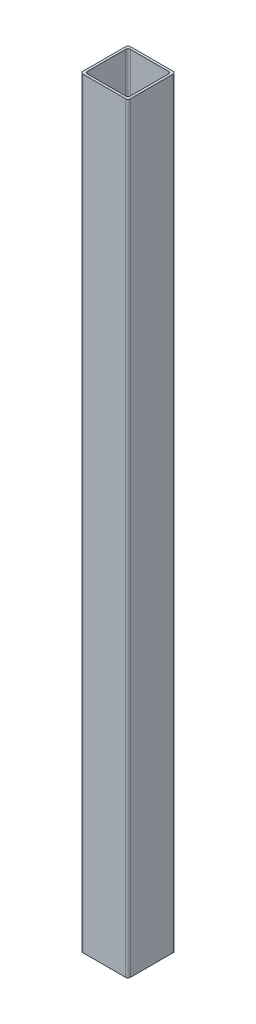
SolidWorks part; units mm, degrees
ref_plane "Спереди" through (0, 0, 0) normal (0, 0, 1) x (1, 0, 0)
ref_plane "Сверху" through (0, 0, 0) normal (0, 1, 0) x (1, 0, 0)
ref_plane "Справа" through (0, 0, 0) normal (1, 0, 0) x (0, 0, -1)
sketch "Эскиз1" plane through (0, 0, 0) normal (0, 1, 0) x (1, 0, 0)
  line L1 (18, -20) -> (-18, -20)
  line L2 (20, -18) -> (20, 18)
  line L3 (18, 20) -> (-18, 20)
  line L4 (-20, -18) -> (-20, 18)
  line L5 (20, -20) -> (-20, 20) construction
  line L6 (20, 20) -> (-20, -20) construction
  line L7 (16, -18) -> (-16, -18)
  line L8 (18, -16) -> (18, 16)
  line L9 (16, 18) -> (-16, 18)
  line L10 (-18, -16) -> (-18, 16)
  line L11 (18, -18) -> (-18, 18) construction
  line L12 (18, 18) -> (-18, -18) construction
  arc A0 (20, 18) -> (18, 20) centre (18, 18) ccw
  arc A1 (18, 16) -> (16, 18) centre (16, 16) ccw
  arc A2 (18, -20) -> (20, -18) centre (18, -18) ccw
  arc A3 (16, -18) -> (18, -16) centre (16, -16) ccw
  arc A4 (-16, -18) -> (-18, -16) centre (-16, -16) cw
  arc A5 (-18, -20) -> (-20, -18) centre (-18, -18) cw
  arc A6 (-16, 18) -> (-18, 16) centre (-16, 16) ccw
  arc A7 (-18, 20) -> (-20, 18) centre (-18, 18) ccw
  point P0 (0, 0)
  point P6 (0, 0)
  dimension "D5" = 2
  dimension "D1" = 40
  dimension "D2" = 40
  dimension "D3" = 2
  dimension "D4" = 2
extrude "Бобышка-Вытянуть1" add sketch "Эскиз1" along normal blind 640
